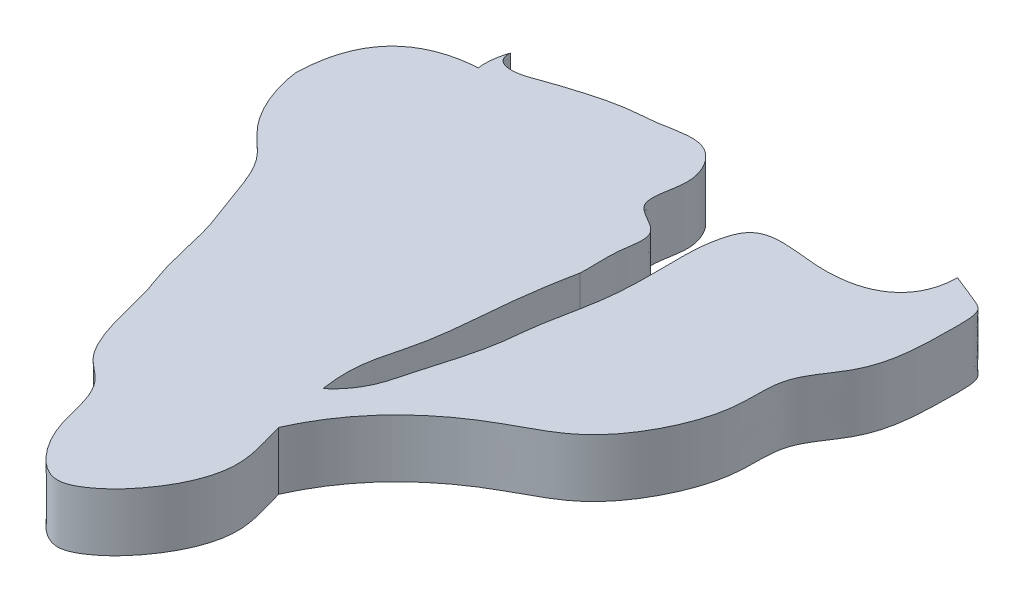
SolidWorks part; units mm, degrees
ref_plane "Front Plane" through (0, 0, 0) normal (0, 0, 1) x (1, 0, 0)
ref_plane "Top Plane" through (0, 0, 0) normal (0, 1, 0) x (1, 0, 0)
ref_plane "Right Plane" through (0, 0, 0) normal (1, 0, 0) x (0, 0, -1)
sketch "Sketch1" plane through (0, 0, 0) normal (0, 1, 0) x (1, 0, 0)
  line L0 (132.9208, 498.8792) -> (664.6039, 498.8792) construction
  spline S0 degree 3 poles (47.4452, 177.9518) (47.0254, 174.6028) (51.7593, 173.3412) (58.5168, 175.9883) (66.5294, 178.5609) (74.6759, 180.5916) (83.6389, 180.9303) (93.9024, 184.3691) (101.5901, 172.2989) (95.3588, 160.0205) (107.8833, 156.8361) (105.1716, 146.4959) (105.9458, 141.0781) (105.7573, 137.4199) knots 0 0 0 0 0.06805 0.126735 0.221277 0.325873 0.379658 0.499724 0.610693 0.730784 0.814837 0.89369 1 1 1 1
  spline S1 degree 3 poles (155.7138, 185.222) (155.4259, 173.1007) (140.4833, 166.9041) (118.937, 172.6125) (115.1926, 160.3303) (115.3483, 149.6177) (115.4446, 134.451) (112.0454, 122.272) (110.8252, 106.92) (107.256, 97.0985) (104.2872, 85.0571) (101.3268, 80.6207) (98.3712, 78.2317) knots 0 0 0 0 0.208505 0.326502 0.372957 0.455667 0.565003 0.69472 0.729434 0.891839 0.917523 1 1 1 1
  spline S2 degree 3 poles (101.3548, 63.7794) (107.1178, 76.7217) (120.4734, 89.8974) (142.3175, 99.8069) (151.7631, 112.7172) (156.6801, 127.2081) (155.0264, 140.7672) (165.9474, 153.3802) (166.4727, 165.3798) (166.4755, 181.7719) (162.7822, 182.2458) (155.7138, 185.222) knots 0 0 0 0 0.265264 0.365208 0.471004 0.575449 0.659468 0.752228 0.920298 0.960402 1 1 1 1
  spline S3 degree 3 poles (155.7138, 185.222) (143.3424, 186.5142) (135.7629, 190.1238) (119.6774, 191.4927) (117.3842, 188.1181) (119.1021, 183.0572) (117.4691, 176.1578) (109.7608, 174.5784) (104.9249, 180.5533) (105.8438, 189.0401) (96.5318, 187.2896) (86.9833, 184.162) (76.6059, 184.9315) (62.0967, 182.3633) (54.5279, 182.9985) (48.6859, 181.0303) knots 0 0 0 0 0.237105 0.256899 0.271012 0.314513 0.364495 0.396714 0.458476 0.498896 0.536122 0.613435 0.730761 0.758905 0.894881 0.894881 0.894881 0.894881
  spline S4 degree 3 poles (84.9542, 23.3748) (72.9575, 20.6745) (71.9674, 25.3606) (66.9703, 32.7264) (63.4633, 41.9395) (58.2122, 48.0409) (50.9968, 58.5561) (50.556, 70.2906) (44.9009, 87.4175) (33.1092, 103.9114) (26.3976, 123.9499) (14.0657, 144.8797) (18.6923, 155.8246) (22.3599, 168.9734) (39.2401, 181.2367) (43.1213, 181.0681) (48.6859, 181.0303) knots 0 0 0 0 0.04448 0.090013 0.138443 0.188153 0.244036 0.300209 0.390948 0.496437 0.613722 0.738952 0.786998 0.806175 0.930725 1 1 1 1
  spline S5 degree 2 poles (24.0375, 145.517) (24.6154, 168.8223) (46.572, 170.2544) knots 0 0 0 1 1 1
  spline S6 degree 3 poles (-2.5807, 150.5978) (25.3813, 187.2619) (71.2737, 199.7007) (119.1491, 205.3389) (188.8296, 188.5694) (163.6488, 122.953) (140.6923, 82.7557) (115.9514, 49.3428) (100.949, 22.7917) (69.9866, 8.4884) (58.9808, 34.5354) (42.6701, 50.0351) (32.6824, 78.02) (22.4132, 112.2265) (-2.5807, 150.5978) (25.3813, 187.2619) (71.2737, 199.7007) knots -0.214288 -0.144168 -0.056107 0 0.077118 0.196257 0.282165 0.391017 0.484824 0.558197 0.611423 0.659102 0.699139 0.739781 0.785712 0.855832 0.943893 1 1.077118 1.196257 1.282165 only from (24.0375, 181.0303) to (24.0375, 181.0303)
  spline S7 degree 2 poles (46.572, 170.2544) (45.9126, 174.769) (48.6859, 181.0303) knots 0.88449 0.88449 0.88449 1 1 1
  spline S8 degree 3 poles (24.0375, 145.517) (24.2622, 143.639) (25.4171, 138.1348) (30.0077, 128.3576) (39.7991, 121.1152) (43.2129, 110.1463) (48.655, 97.0574) (49.9673, 86.7279) (54.646, 75.4111) (57.5935, 57.5488) (72.352, 47.8516) (69.1404, 35.825) (82.724, 21.3135) (91.461, 26.0846) (99.36, 34.146) (106.4591, 48.0552) (101.5336, 62.2605) (98.8404, 74.4776) (96.8682, 87.5544) (101.8022, 102.1432) (102.7904, 119.2975) (104.336, 130.4469) (105.7536, 137.4018) (105.7573, 137.4199) knots 0.084883 0.084883 0.084883 0.084883 0.10777 0.154078 0.187829 0.232552 0.269709 0.335229 0.347597 0.388302 0.400297 0.462464 0.490432 0.503111 0.523547 0.568461 0.596541 0.621395 0.653634 0.683153 0.723781 0.766209 0.766319 0.766319 0.766319 0.766319
extrude "Boss-Extrude1" add sketch "Sketch1" along normal blind 15 contours S5 S8 S0 S7 | S8 S2 S1
